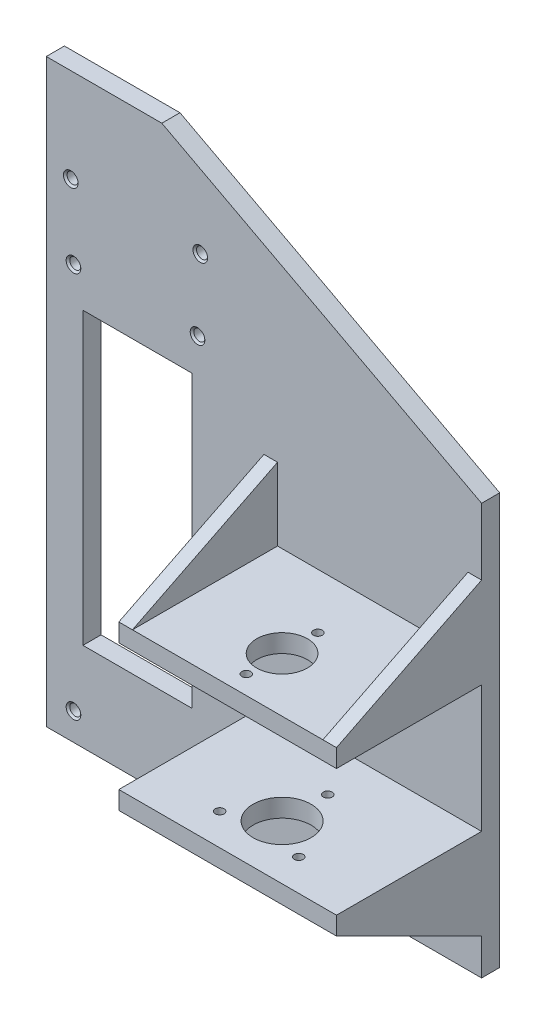
SolidWorks part; units mm, degrees
ref_plane "Front Plane" through (0, 0, 0) normal (0, 0, 1) x (1, 0, 0)
ref_plane "Top Plane" through (0, 0, 0) normal (0, 1, 0) x (1, 0, 0)
ref_plane "Right Plane" through (0, 0, 0) normal (1, 0, 0) x (0, 0, -1)
sketch "Sketch1" plane through (0, 0, 0) normal (0, 0, 1) x (1, 0, 0)
  line L1 (-76.2, 101.6) -> (76.2, 101.6)
  line L2 (-76.2, 101.6) -> (-76.2, -101.6)
  line L3 (-76.2, -101.6) -> (76.2, -101.6)
  line L4 (76.2, 101.6) -> (76.2, -101.6)
  line L5 (-76.2, 101.6) -> (76.2, -101.6) construction
  line L6 (-76.2, -101.6) -> (76.2, 101.6) construction
  point P0 (0, 0)
  dimension "D1" = 152.4
  dimension "D2" = 203.2
extrude "base" add sketch "Sketch1" along normal blind 6.35
sketch "Sketch2" plane through (0, 0, 6.35) normal (0, 0, 1) x (1, 0, 0)
  line L0 (38.1, -60.325) -> (38.1, -9.525) construction
  line L1 (0, -6.35) -> (76.2, -6.35)
  line L2 (0, -6.35) -> (0, -12.7)
  line L3 (0, -12.7) -> (76.2, -12.7)
  line L4 (76.2, -6.35) -> (76.2, -12.7)
  line L5 (0, -6.35) -> (76.2, -12.7) construction
  line L6 (0, -12.7) -> (76.2, -6.35) construction
  line L7 (0, -57.15) -> (76.2, -57.15)
  line L8 (0, -57.15) -> (0, -63.5)
  line L9 (0, -63.5) -> (76.2, -63.5)
  line L10 (76.2, -57.15) -> (76.2, -63.5)
  line L11 (0, -57.15) -> (76.2, -63.5) construction
  line L12 (0, -63.5) -> (76.2, -57.15) construction
  line L14 (76.2, -101.6) -> (76.2, 101.6) construction
  line L15 (-76.2, -101.6) -> (76.2, -101.6) construction
  point P0 (38.1, -9.525)
  point P5 (38.1, -60.325)
  dimension "D1" = 50.8
  dimension "D2" = 76.2
  dimension "D3" = 6.35
  dimension "D4" = 0
  dimension "D5" = 38.1
extrude "mount walls" add sketch "Sketch2" along normal blind 50.8
sketch "Sketch3" plane through (76.2, 0, 0) normal (1, 0, 0) x (0, 0, -1)
  line L0 (-6.35, -88.9) -> (-57.15, -63.5)
  line L1 (-57.15, -63.5) -> (-6.35, -63.5)
  line L2 (-6.35, -63.5) -> (-6.35, -88.9)
  line L3 (-57.15, -6.35) -> (-6.35, 19.05)
  line L4 (-6.35, -6.35) -> (-6.35, 101.6) construction
  line L5 (-6.35, 19.05) -> (-6.35, -6.35)
  line L6 (-6.35, -6.35) -> (-57.15, -6.35)
  dimension "D1" = 25.4
  dimension "D2" = 25.4
extrude "mount support" add sketch "Sketch3" against normal blind 4.7625
ref_plane "Plane1" through (38.1, 0, 0) normal (1, 0, 0) x (0, 0, -1)
mirror "Mirror1" about plane through (38.1, 0, 0) normal (1, 0, 0) of "mount support"
hole_wizard "#24 (0.152) Diameter Hole1" positions "Sketch4" profile "Sketch5" hole size "#24" standard "ANSI Inch" end condition through all
sketch "Sketch4" plane through (0, 0, 6.35) normal (0, 0, 1) x (1, 0, 0)
  line L0 (-66.675, -92.075) -> (-23.241, -92.075)
  line L1 (-23.241, -92.075) -> (-23.241, 43.307)
  line L3 (-23.241, 43.307) -> (-66.675, 43.307)
  line L4 (-66.675, 43.307) -> (-66.675, -92.075)
  line L5 (-22.2885, 68.707) -> (-67.6275, 68.707)
  line L6 (-44.958, 68.707) -> (-44.958, 43.307)
  line L7 (-76.2, -101.6) -> (76.2, -101.6) construction
  line L8 (-76.2, 101.6) -> (-76.2, -101.6) construction
  point P0 (-66.675, -92.075)
  point P2 (-66.675, 43.307)
  point P4 (-23.241, 43.307)
  point P6 (-23.241, -92.075)
  point P8 (-67.6275, 68.707)
  point P10 (-22.2885, 68.707)
  dimension "D1" = 135.382
  dimension "D2" = 43.434
  dimension "D3" = 45.339
  dimension "D4" = 9.525
  dimension "D5" = 9.525
  dimension "D6" = 25.4
sketch "Sketch5" plane through (-66.675, -92.075, 6.35) normal (1, 0, 0) x (0, -1, 0)
  line L0 (0, 0) -> (0, 6.35)
  line L1 (0, 6.35) -> (1.9304, 6.35)
  line L2 (1.9304, 6.35) -> (1.9304, 0.635)
  line L3 (1.9304, 0.635) -> (2.5654, 0)
  line L5 (2.5654, 0) -> (0, 0)
  line L6 (-1.9304, 0.635) -> (-2.5654, 0) construction
  line L11 (0, -6.35) -> (0, 107.95) construction
  dimension "Thru Hole Dia." = 3.8608
  dimension "Thru Hole Depth" = 6.35
  dimension "Near C'Sink Dia." = 5.1308
  dimension "Near C'Sink Angle" = 90
sketch "Sketch6" plane through (0, -12.7, 0) normal (0, -1, 0) x (1, 0, 0)
  line L0 (38.1, 25.5714) -> (38.1, 50.6285) construction
  line L1 (0, 57.15) -> (76.2, 57.15) construction
  line L2 (0, 38.1) -> (76.2, 38.1) construction
  line L3 (0, 57.15) -> (0, 6.35) construction
  line L4 (76.2, 57.15) -> (76.2, 6.35) construction
  circle A0 centre (38.1, 38.1) radius 8.89
  circle A1 centre (38.1, 50.6285) radius 1.55
  circle A2 centre (38.1, 25.5714) radius 1.55
  point P6 (38.1, 38.1)
  point P8 (38.1, 38.1)
  dimension "D1" = 17.78
  dimension "D2" = 3.1
  dimension "D3" = 25.0571
  dimension "D4" = 19.05
extrude "Cut-Extrude1" cut sketch "Sketch6" against normal through all
sketch "Sketch7" plane through (0, -57.15, 0) normal (0, 1, 0) x (1, 0, 0)
  line L0 (38.1, -38.1) -> (71.0956, -57.15) construction
  line L1 (76.2, -57.15) -> (0, -57.15) construction
  line L2 (38.1, -38.1) -> (5.1044, -57.15) construction
  line L3 (38.1, -38.1) -> (38.1, 0) construction
  line L4 (22.7076, -46.0919) -> (53.4924, -46.0919) construction
  circle A0 centre (38.1, -38.1) radius 10.16
  circle A1 centre (38.1, -38.1) radius 8.89 construction
  circle A2 centre (24.2576, -46.0919) radius 1.55
  circle A3 centre (38.1, -22.1162) radius 1.55
  circle A4 centre (51.9424, -46.0919) radius 1.55
  circle A6 centre (38.1, -38.1) radius 15.9838 construction
  dimension "D1" = 20.32
  dimension "D4" = 3.1
  dimension "D5" = 30.7848
  dimension "D2" = 120
  dimension "D3" = 120
extrude "Cut-Extrude2" cut sketch "Sketch7" against normal up to surface (6.35 mm away) up to face at (38.1, -63.5, 31.75)
sketch "Sketch8" plane through (0, 0, 6.35) normal (0, 0, 1) x (1, 0, 0)
  line L0 (76.2, 42.3381) -> (-35.7443, 101.6)
  line L1 (76.2, 19.05) -> (76.2, 101.6) construction
  line L2 (76.2, 101.6) -> (-76.2, 101.6) construction
  line L3 (-35.7443, 101.6) -> (76.2, 101.6)
  line L4 (76.2, 101.6) -> (76.2, 42.3381)
  line L6 (-63.3619, -70.5225) -> (-25.2619, -70.5225)
  line L7 (-63.3619, -70.5225) -> (-63.3619, 31.0775)
  line L8 (-63.3619, 31.0775) -> (-25.2619, 31.0775)
  line L9 (-25.2619, -70.5225) -> (-25.2619, 31.0775)
  line L10 (-63.3619, -70.5225) -> (-25.2619, 31.0775) construction
  line L11 (-63.3619, 31.0775) -> (-25.2619, -70.5225) construction
  point P6 (-44.3119, -19.7225)
  dimension "D1" = 101.6
  dimension "D2" = 38.1
extrude "Cut-Extrude3" cut sketch "Sketch8" against normal up to next
